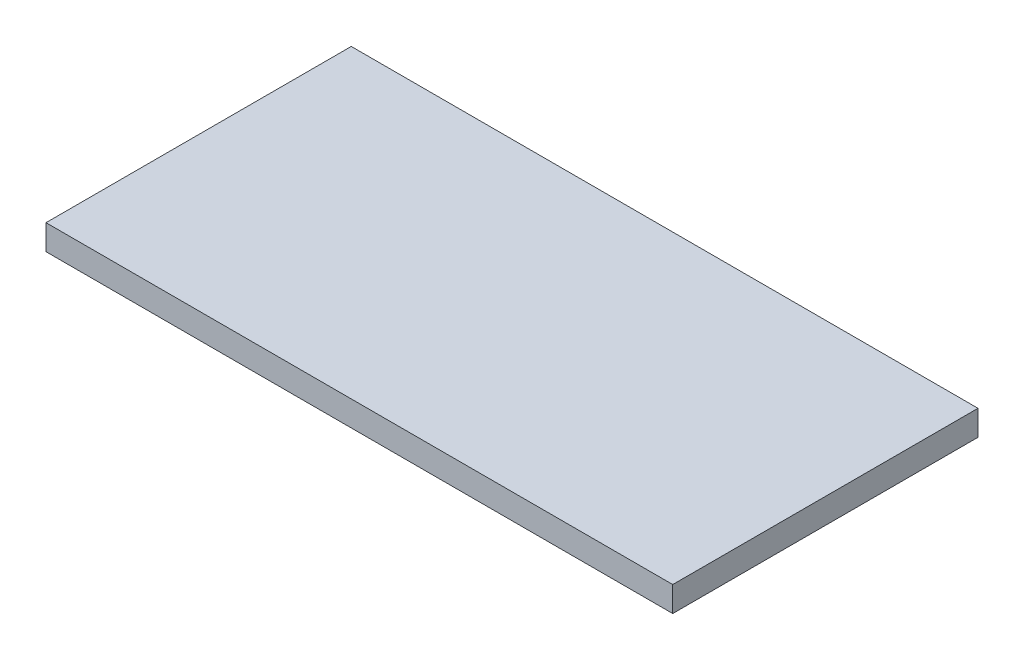
SolidWorks part; units mm, degrees
material "AISI 1020"
ref_plane "Front Plane" through (0, 0, 0) normal (0, 0, 1) x (1, 0, 0)
ref_plane "Top Plane" through (0, 0, 0) normal (0, 1, 0) x (1, 0, 0)
ref_plane "Right Plane" through (0, 0, 0) normal (1, 0, 0) x (0, 0, -1)
sketch "Sketch1" plane through (0, 0, 0) normal (0, 1, 0) x (1, 0, 0)
  line L1 (-124.6102, -60.6916) -> (124.6102, -60.6916)
  line L2 (-124.6102, -60.6916) -> (-124.6102, 60.6916)
  line L3 (-124.6102, 60.6916) -> (124.6102, 60.6916)
  line L4 (124.6102, -60.6916) -> (124.6102, 60.6916)
  line L5 (-124.6102, -60.6916) -> (124.6102, 60.6916) construction
  line L6 (-124.6102, 60.6916) -> (124.6102, -60.6916) construction
  point P0 (0, 0)
extrude "Boss-Extrude1" add sketch "Sketch1" along normal blind 10
